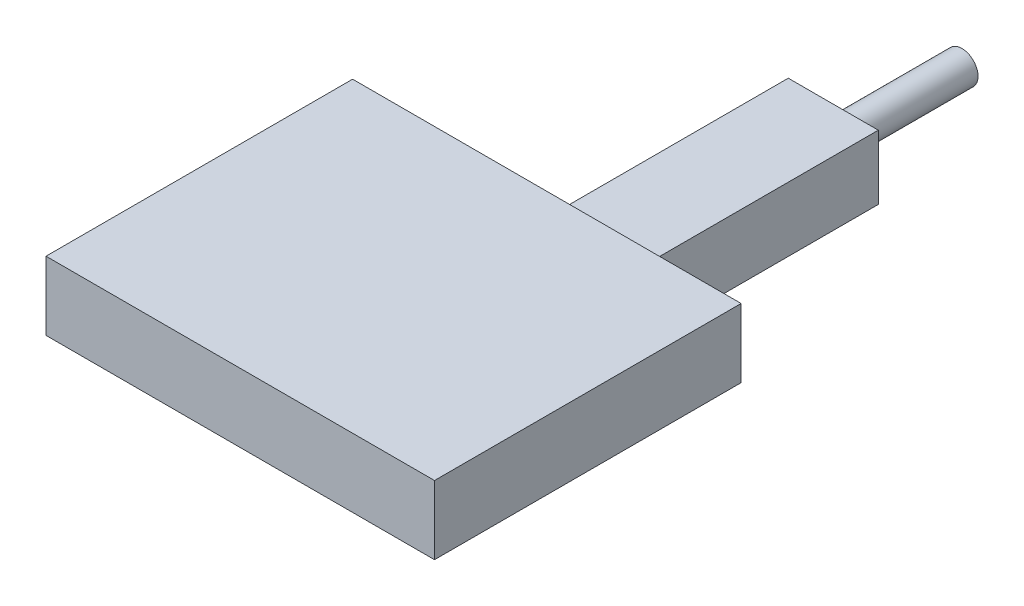
SolidWorks part; units mm, degrees
ref_plane "Front Plane" through (0, 0, 0) normal (0, 0, 1) x (1, 0, 0)
ref_plane "Top Plane" through (0, 0, 0) normal (0, 1, 0) x (1, 0, 0)
ref_plane "Right Plane" through (0, 0, 0) normal (1, 0, 0) x (0, 0, -1)
sketch "Sketch1" plane through (0, 0, 0) normal (0, 1, 0) x (1, 0, 0)
  line L1 (-45.3, 35.75) -> (45.3, 35.75)
  line L2 (-45.3, 35.75) -> (-45.3, -35.75)
  line L3 (-45.3, -35.75) -> (45.3, -35.75)
  line L4 (45.3, 35.75) -> (45.3, -35.75)
  line L5 (-45.3, 35.75) -> (45.3, -35.75) construction
  line L6 (-45.3, -35.75) -> (45.3, 35.75) construction
  point P0 (0, 0)
  dimension "D1" = 90.6
  dimension "D2" = 71.5
extrude "Boss-Extrude1" add sketch "Sketch1" along normal blind 16
sketch "Sketch2" plane through (0, 0, 0) normal (0, 1, 0) x (1, 0, 0)
  line L0 (45.3, 35.75) -> (-45.3, 35.75) construction
  line L1 (25.3, 35.75) -> (4.3, 35.75)
  line L2 (25.3, 35.75) -> (25.3, 87.75)
  line L3 (25.3, 87.75) -> (4.3, 87.75)
  line L4 (4.3, 35.75) -> (4.3, 87.75)
  dimension "D1" = 20
  dimension "D2" = 21
  dimension "D3" = 52
extrude "Boss-Extrude2" add sketch "Sketch2" along normal blind 15
sketch "Sketch3" plane through (0, 0, -87.75) normal (0, 0, -1) x (-1, 0, 0)
  circle A0 centre (-14.8, 7.5) radius 3.75
  dimension "D1" = 7.5
extrude "Boss-Extrude3" add sketch "Sketch3" along normal blind 30
